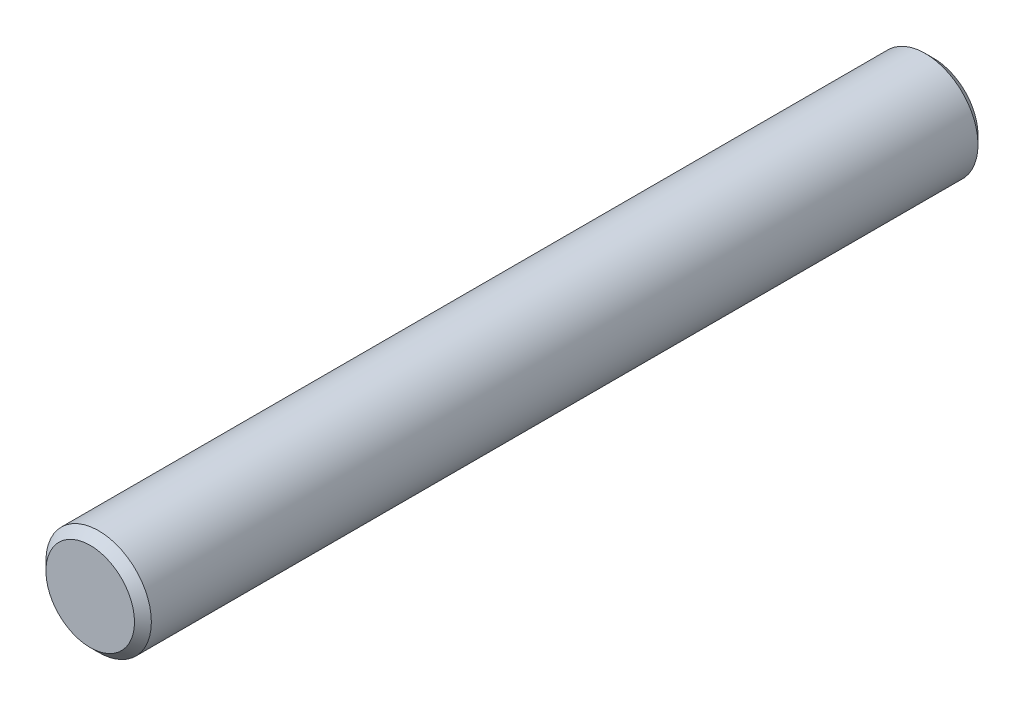
SolidWorks part; units mm, degrees
ref_plane "Front Plane" through (0, 0, 0) normal (0, 0, 1) x (1, 0, 0)
ref_plane "Top Plane" through (0, 0, 0) normal (0, 1, 0) x (1, 0, 0)
ref_plane "Right Plane" through (0, 0, 0) normal (1, 0, 0) x (0, 0, -1)
sketch "Sketch1" plane through (0, 0, 0) normal (0, 0, 1) x (1, 0, 0)
  circle A0 centre (0, 0) radius 12.5
  dimension "D1" = 25
extrude "Boss-Extrude1" add sketch "Sketch1" along normal blind 200
chamfer "Chamfer1" distance 2 angle 45 2 edges at (12.5, 0, 0) (12.5, 0, 200)
